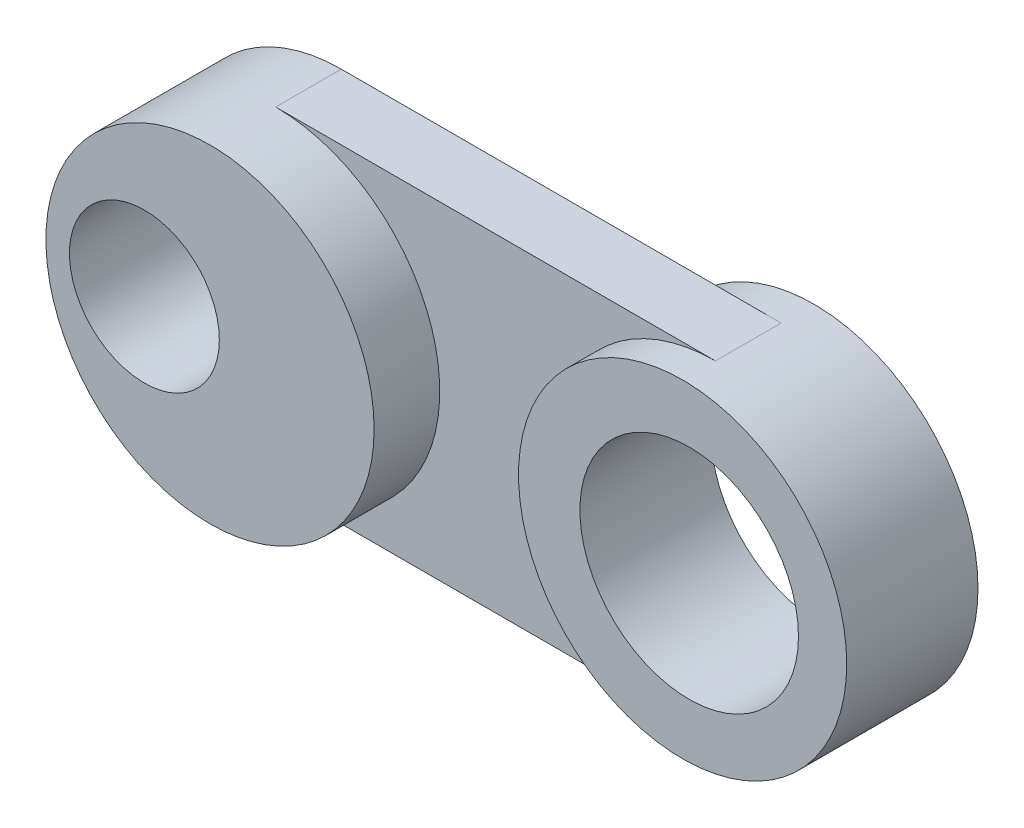
SolidWorks part; units mm, degrees
material "Custom Plastic"
ref_plane "Front Plane" through (0, 0, 0) normal (0, 0, 1) x (1, 0, 0)
ref_plane "Top Plane" through (0, 0, 0) normal (0, 1, 0) x (1, 0, 0)
ref_plane "Right Plane" through (0, 0, 0) normal (1, 0, 0) x (0, 0, -1)
sketch "Sketch1" plane through (0, 0, 0) normal (0, 0, 1) x (1, 0, 0)
  line L0 (0, 12.7) -> (17.018, 12.7)
  line L1 (0, 0) -> (17.018, 0)
  arc A0 (0, 0) -> (0, 12.7) centre (0, 6.35) cw
  arc A1 (17.018, 12.7) -> (17.018, 0) centre (17.018, 6.35) cw
  circle A2 centre (-2.54, 6.35) radius 2.9
  circle A3 centre (17.272, 6.35) radius 4.2291
  dimension "D1" = 6.35
  dimension "D2" = 17.018
  dimension "D3" = 5.8
  dimension "D4" = 2.54
  dimension "D7" = 8.4582
  dimension "D5" = 0.254
  dimension "D6" = 6.35
extrude "Boss-Extrude1" add sketch "Sketch1" along normal mid plane 2.54
sketch "Sketch2" plane through (0, 0, 1.27) normal (0, 0, 1) x (1, 0, 0)
  circle A0 centre (0, 6.35) radius 6.35
  arc A1 (0, 12.7) -> (0, 0) centre (0, 6.35) ccw construction
  arc M2 (0, 12.7) -> (0, 0) centre (0, 6.35) ccw
  circle M7 centre (-2.54, 6.35) radius 2.9
extrude "Boss-Extrude2" add sketch "Sketch2" along normal blind 2.54 contours A0 M2 M7
sketch "Sketch3" plane through (0, 0, 3.81) normal (0, 0, 1) x (1, 0, 0)
  line L0 (-2.9035, 3.4729) -> (-2.54, 3.55)
  line L1 (-2.54, 3.55) -> (-2.1765, 3.4729)
  line L4 (-2.54, 9.25) -> (-2.54, 3.45) construction
  line L5 (-3.2363, 3.638) -> (-2.9035, 3.4729)
  line L6 (-3.6076, 3.6536) -> (-3.2363, 3.638)
  line L7 (-3.8889, 3.8963) -> (-3.6076, 3.6536)
  line L8 (-4.2446, 4.0039) -> (-3.8889, 3.8963)
  line L9 (-4.4567, 4.3089) -> (-4.2446, 4.0039)
  line L10 (-4.7745, 4.5015) -> (-4.4567, 4.3089)
  line L11 (-4.9041, 4.8497) -> (-4.7745, 4.5015)
  line L12 (-5.164, 5.1152) -> (-4.9041, 4.8497)
  line L13 (-5.203, 5.4848) -> (-5.164, 5.1152)
  line L14 (-5.3886, 5.8066) -> (-5.203, 5.4848)
  line L15 (-5.3345, 6.1742) -> (-5.3886, 5.8066)
  line L16 (-5.4343, 6.5321) -> (-5.3345, 6.1742)
  line L17 (-5.2904, 6.8747) -> (-5.4343, 6.5321)
  line L18 (-5.2981, 7.2461) -> (-5.2904, 6.8747)
  line L19 (-5.0735, 7.5422) -> (-5.2981, 7.2461)
  line L20 (-4.9886, 7.9039) -> (-5.0735, 7.5422)
  line L21 (-4.6974, 8.1348) -> (-4.9886, 7.9039)
  line L22 (-4.5252, 8.464) -> (-4.6974, 8.1348)
  line L23 (-4.1858, 8.6152) -> (-4.5252, 8.464)
  line L24 (-3.9371, 8.8913) -> (-4.1858, 8.6152)
  line L25 (-3.5707, 8.9534) -> (-3.9371, 8.8913)
  line L26 (-3.2612, 9.1589) -> (-3.5707, 8.9534)
  line L27 (-2.8909, 9.1279) -> (-3.2612, 9.1589)
  line L28 (-2.54, 9.25) -> (-2.8909, 9.1279)
  line L29 (-2.1891, 9.1279) -> (-2.54, 9.25)
  line L30 (-1.8188, 9.1589) -> (-2.1891, 9.1279)
  line L31 (-1.5093, 8.9534) -> (-1.8188, 9.1589)
  line L32 (-1.1429, 8.8913) -> (-1.5093, 8.9534)
  line L33 (-0.8942, 8.6152) -> (-1.1429, 8.8913)
  line L34 (-0.5548, 8.464) -> (-0.8942, 8.6152)
  line L35 (-0.3826, 8.1348) -> (-0.5548, 8.464)
  line L36 (-0.0914, 7.9039) -> (-0.3826, 8.1348)
  line L37 (-0.0065, 7.5422) -> (-0.0914, 7.9039)
  line L38 (0.2181, 7.2461) -> (-0.0065, 7.5422)
  line L39 (0.2104, 6.8747) -> (0.2181, 7.2461)
  line L40 (0.3543, 6.5321) -> (0.2104, 6.8747)
  line L41 (0.2545, 6.1742) -> (0.3543, 6.5321)
  line L42 (0.3086, 5.8066) -> (0.2545, 6.1742)
  line L43 (0.123, 5.4848) -> (0.3086, 5.8066)
  line L44 (0.084, 5.1152) -> (0.123, 5.4848)
  line L45 (-0.1759, 4.8497) -> (0.084, 5.1152)
  line L46 (-0.3055, 4.5015) -> (-0.1759, 4.8497)
  line L47 (-0.6233, 4.3089) -> (-0.3055, 4.5015)
  line L48 (-0.8354, 4.0039) -> (-0.6233, 4.3089)
  line L49 (-1.1911, 3.8963) -> (-0.8354, 4.0039)
  line L50 (-1.4724, 3.6536) -> (-1.1911, 3.8963)
  line L51 (-1.8437, 3.638) -> (-1.4724, 3.6536)
  line L52 (-2.1765, 3.4729) -> (-1.8437, 3.638)
  circle A0 centre (-2.54, 6.35) radius 2.9 construction
  circle A1 centre (-2.54, 6.35) radius 2.8 construction
  point P83 (-2.54, 6.35)
  circle M5 centre (-2.54, 6.35) radius 2.9
  dimension "D2" = 5.6
  dimension "D1" = 25
extrude "Boss-Extrude3" [suppressed] add sketch "Sketch3" against normal up to surface (5.08 mm away) contours L22 L21 M5 | L20 L19 M5 | L18 L17 M5 | L16 L15 M5 | L14 L13 M5 | L12 L11 M5 | L10 L9 M5 | L8 L7 M5 | L6 L5 M5 | L1 L0 M5 | L52 L51 M5 | L50 L49 M5 | L48 L47 M5 | L46 L45 M5 | L44 L43 M5 | L42 L41 M5 | L40 L39 M5 | L38 L37 M5 | L36 L35 M5 | L34 L33 M5 | L32 L31 M5 | L30 L29 M5 | L28 L27 M5 | L26 L25 M5 | L24 L23 M5
sketch "Sketch4" plane through (0, 0, 0) normal (0, 0, 1) x (1, 0, 0)
  circle A0 centre (17.272, 6.35) radius 4.2291
  circle A1 centre (17.272, 6.35) radius 4.2291 construction
  circle A2 centre (17.018, 6.35) radius 6.35
  arc A3 (17.018, 0) -> (17.018, 12.7) centre (17.018, 6.35) ccw construction
extrude "Boss-Extrude4" add sketch "Sketch4" along normal mid plane 5.08
